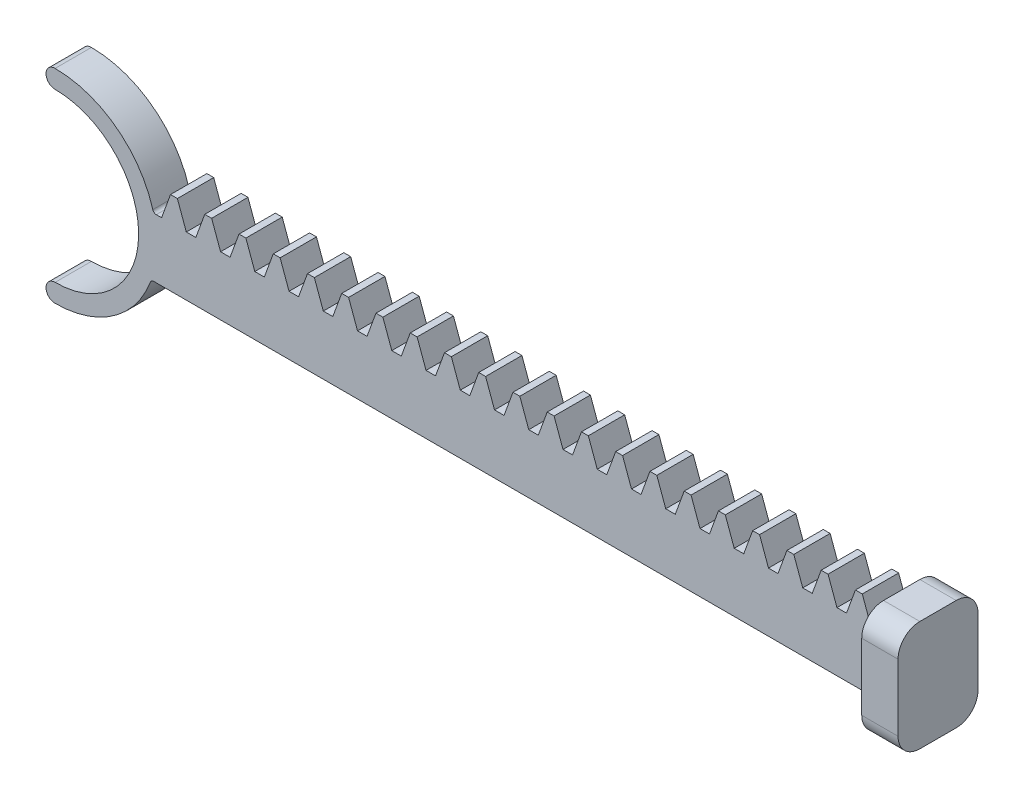
SolidWorks part; units mm, degrees
extrude "Blank" add sketch "BlankSke" against normal blind 5
sketch "BlankSke" plane through (0, 0, 0) normal (0, 0, 1) x (1, 0, 0)
  line L1 (0, 0) -> (100, 0)
  line L2 (0, 0) -> (0, 11.5)
  line L3 (0, 11.5) -> (100, 11.5)
  line L4 (100, 0) -> (100, 11.5)
  dimension "Length" = 100
  dimension "Blank_height" = 11.5
ref_plane "Plane1" through (0, 0, 0) normal (0, 0, 1) x (1, 0, 0)
ref_plane "Plane2" through (0, 0, 0) normal (0, 1, 0) x (1, 0, 0)
ref_plane "Plane3" through (0, 0, 0) normal (1, 0, 0) x (0, 0, -1)
other "Configuration Table"
sketch "HoldingSke" plane through (0, 0, 0) normal (0, 1, 0) x (1, 0, 0)
  line L0 (0, 0) -> (0.0928, 0.6602)
  line L1 (-15, 0) -> (100, 0) construction
  line L2 (0, 0) -> (-2.1039, 2.3779)
  line L3 (0, 0) -> (-11.863, 4.5341)
  line L4 (0, 0) -> (7.9495, 3.3743)
  line L5 (0, 0) -> (-23.7986, -8.8762)
  line L6 (0, 0) -> (-10.5278, -7.1032)
  line L9 (-71.009, 38.7566) -> (22.9603, 72.9586)
  line L10 (-76.2, 3.8779) -> (-66.2, 3.8779)
  line L11 (0, 0) -> (-5, 0)
  line L12 (-76.2, 101.6) -> (-76.147, 101.6)
  line L13 (24.9733, 27.94) -> (52.9518, 28.4284)
  line L14 (24.9733, 27.94) -> (24.9743, 27.94)
  line L15 (24.9733, 27.94) -> (100.4006, 29.5858)
  circle A0 centre (0, 0) radius 19.05
  circle A1 centre (0, 0) radius 5
  circle A2 centre (0, 0) radius 12.7
  dimension "MPH" = 10
  dimension "Diameter" = 38.1
  dimension "Num_teeth" = 23
  dimension "Pitch" = 0.6667
  dimension "Show_teeth" = 998
  dimension "Thickness" = 12.7
  dimension "Ap" = 20
  dimension "Pitch_height" = 10
  dimension "Width" = 5
  dimension "Backlash" = 0.053
  dimension "Addendum_fac" = 1
  dimension "Dedendum_fac" = 1.25
  dimension "Clearance_fac" = 0.25
  dimension "Dedendum_add" = 0.001
  dimension "Length" = 100
  dimension "Module" = 1.5
sketch "TooCutSkeIll" plane through (0, 0, 0) normal (0, 0, 1) x (1, 0, 0)
  line L0 (-1.8687, 11.4605) -> (-0.7447, 8.3724)
  line L1 (-0.3914, 8.125) -> (0.3914, 8.125)
  line L2 (0.7447, 8.3724) -> (1.8687, 11.4605)
  line L3 (100, 11.5) -> (0, 11.5) construction
  line L4 (0, 0) -> (0, 64.897) construction
  line L5 (-13.208, 10) -> (12.954, 10) construction
  line L6 (0, 0) -> (100, 0) construction
  line L7 (1.3371, 10) -> (1.3371, 48.7463) construction
  line L8 (-1.3371, 10) -> (-1.3371, 48.7463) construction
  line L9 (1.9251, 11.5) -> (1.9251, 11.5254)
  line L10 (-1.9251, 11.5) -> (-1.9251, 11.5254)
  line L11 (-1.9251, 11.5254) -> (1.9251, 11.5254)
  arc A0 (0.3914, 8.125) -> (0.7447, 8.3724) centre (0.3914, 8.501) ccw
  arc A1 (-0.7447, 8.3724) -> (-0.3914, 8.125) centre (-0.3914, 8.501) ccw
  arc A2 (1.9251, 11.5) -> (1.8687, 11.4605) centre (1.9251, 11.44) ccw
  arc A3 (-1.8687, 11.4605) -> (-1.9251, 11.5) centre (-1.9251, 11.44) ccw
  dimension "Pitch_height" = 10
  dimension "Addendum_plus" = 1.5254
  dimension "Pressure_angle" = 20
  dimension "Gap_width" = 2.6742
  dimension "Dedendum" = 1.875
extrude "ToothCutIll" [suppressed] cut sketch "TooCutSkeIll" against normal through all
sketch "TooCutSkeSim" plane through (0, 0, 0) normal (0, 0, 1) x (1, 0, 0)
  line L0 (0.6547, 8.125) -> (-0.6547, 8.125)
  line L1 (1.8923, 11.5254) -> (0.6547, 8.125)
  line L2 (0, 17.4625) -> (0, 53.467) construction
  line L3 (1.8923, 11.5254) -> (-1.8923, 11.5254)
  line L6 (-1.8923, 11.5254) -> (-0.6547, 8.125)
  line L9 (-1.3371, 10) -> (1.3371, 10) construction
  line L10 (0, 0) -> (100, 0) construction
  line L11 (1.3371, 10) -> (1.3371, 53.467) construction
  line L12 (-1.3371, 10) -> (-1.3371, 53.467) construction
  dimension "Pitch_height" = 10
  dimension "Addendum_plus" = 1.5254
  dimension "Pressure_angle" = 20
  dimension "Gap_width" = 2.6742
  dimension "Dedendum" = 1.875
extrude "ToothCutSim" cut sketch "TooCutSkeSim" against normal through all
pattern_linear "TeethCuts" count 22 spacing 4.7124 along (1, 0, 0) of "ToothCutIll", "ToothCutSim"
sketch "Esquisse1" plane through (100, 0, 0) normal (1, 0, 0) x (0, 0, -1)
  line L0 (5, 12.1833) -> (0, 12.1833)
  line L1 (-3, 9.1833) -> (-3, 0)
  line L2 (0, -3) -> (5, -3)
  line L3 (8, 0) -> (8, 9.1833)
  line L4 (5, 9.1833) -> (0, 9.1833)
  line L5 (0, 9.1833) -> (0, 0)
  line L6 (0, 0) -> (5, 0)
  line L7 (5, 0) -> (5, 9.1833)
  line L8 (5, 9.1833) -> (0, 9.1833)
  line L9 (0, 9.1833) -> (0, 0) construction
  line L10 (0, 0) -> (5, 0)
  line L11 (5, 0) -> (5, 9.1833)
  line L12 (8, 12.1833) -> (-3, 12.1833) construction
  line L13 (8, -3) -> (8, 12.1833) construction
  line L14 (-3, -3) -> (8, -3) construction
  line L15 (-3, 12.1833) -> (-3, -3) construction
  arc A0 (5, 12.1833) -> (8, 9.1833) centre (5, 9.1833) cw
  arc A1 (5, -3) -> (8, 0) centre (5, 0) ccw
  arc A2 (-3, 0) -> (0, -3) centre (0, 0) ccw
  arc A3 (0, 12.1833) -> (-3, 9.1833) centre (0, 9.1833) ccw
  line M9 (5, 9.1833) -> (0, 9.1833)
  line M10 (0, 9.1833) -> (0, 0)
  line M11 (0, 0) -> (5, 0)
  line M12 (5, 0) -> (5, 9.1833)
  dimension "D3" = 3
  dimension "D1" = 0
  dimension "D2" = 3
extrude "Boss.-Extru.1" add sketch "Esquisse1" along normal blind 5 contours M12 M9 M10 M11 | L2 L3 L0 L1 M9 M12 M11 M10
sketch "Esquisse2" plane through (0, 0, -5) normal (0, 0, -1) x (-1, 0, 0)
  line L0 (-100, 4.5916) -> (14, 4.5916) construction
  line L1 (-100, 0) -> (-100, 9.1833) construction
  line L2 (0, 8.125) -> (0, 0) construction
  line L3 (0, 0) -> (-100, 0) construction
  line L4 (14, 25.3023) -> (14, -17.91) construction
  line L5 (0, 8.125) -> (0.0723, 8.125)
  line L6 (0, 0) -> (0.4234, 0)
  line L7 (0, 8.125) -> (0, 0)
  arc A0 (14, 18.5916) -> (0.5525, 8.4859) centre (14, 4.5916) ccw
  arc A1 (14, 16.0916) -> (14, -6.9084) centre (14, 4.5916) ccw
  arc A2 (14, 18.5916) -> (14, 16.0916) centre (14, 17.3416) cw
  arc A3 (14, -6.9084) -> (14, -9.4084) centre (14, -8.1584) cw
  arc A4 (0.8915, -0.3244) -> (14, -9.4084) centre (14, 4.5916) ccw
  arc A5 (14, 18.5916) -> (14, -9.4084) centre (14, 4.5916) ccw construction
  arc A6 (0.4234, 0) -> (0.8915, -0.3244) centre (0.4234, -0.5) cw
  arc A7 (0.0723, 8.125) -> (0.5525, 8.4859) centre (0.0723, 8.625) ccw
  point P23 (0.7744, 0)
  dimension "D1" = 28
  dimension "D3" = 0.5
  dimension "D2" = 2.5
extrude "Boss.-Extru.2" add sketch "Esquisse2" against normal blind 5
equation "' \"Module@HoldingSke\" = 6.35"
equation "' \"Num_teeth@HoldingSke\" = 12"
equation "' \"Ap@HoldingSke\" =  20"
equation "' \"Ap@HoldingSke\" = 20"
equation "' \"Width@HoldingSke\" = 0.25 * 25.4"
equation "' \"Show_teeth@HoldingSke\" = 500"
equation "' \"Backlash@HoldingSke\" = 0.009 * 25.4"
equation "' \"Addendum_fac@HoldingSke\" = 1.0"
equation "' \"Dedendum_fac@HoldingSke\" = 1.25"
equation "' \"Dedendum_add@HoldingSke\" = 0.00005 * 25.4"
equation "' \"Clearance_fac@HoldingSke\" = 0.25"
equation "' \"Pitch_height@HoldingSke\" = 1 * 25.4"
equation "' \"Length@HoldingSke\" = 4.71 * 25.4"
equation "\"Pitch@HoldingSke\" = 1 / \"Module@HoldingSke\""
equation "\"MPH@HoldingSke\" = \"Dedendum_fac@HoldingSke\" / \"Pitch@HoldingSke\" + 2 * \"Dedendum_add@HoldingSke\" + 0.002 * 25.4"
equation "\"MPH@HoldingSke\" = ((sgn( \"MPH@HoldingSke\" - \"Pitch_height@HoldingSke\")+1)*( \"MPH@HoldingSke\" - \"Pitch_height@HoldingSke\"))/2 + \"Pitch_height@HoldingSke\""
equation "\"Blank_height@BlankSke\" = \"Pitch_height@HoldingSke\" + \"Addendum_fac@HoldingSke\"  / \"Pitch@HoldingSke\" "
equation "\"Length@BlankSke\" =  \"Length@HoldingSke\""
equation "\"Face_width@Blank\" = \"Width@HoldingSke\""
equation "\"Pressure_angle@TooCutSkeIll\" = \"Ap@HoldingSke\""
equation "\"Addendum_plus@TooCutSkeIll\" =  \"Addendum_fac@HoldingSke\"  / \"Pitch@HoldingSke\" + 0.001 *25.4"
equation "\"Dedendum@TooCutSkeIll\" = \"Dedendum_fac@HoldingSke\"  / \"Pitch@HoldingSke\""
equation "\"Pitch_height@TooCutSkeIll\" =  \"MPH@HoldingSke\""
equation "\"Gap_width@TooCutSkeIll\" = 3.14159265 / 2 / \"Pitch@HoldingSke\" + 6 * \"Backlash@HoldingSke\""
equation "\"Pressure_angle@TooCutSkeSim\" = \"Ap@HoldingSke\""
equation "\"Addendum_plus@TooCutSkeSim\" =  \"Addendum_fac@HoldingSke\"  / \"Pitch@HoldingSke\" + 0.001 * 25.4"
equation "\"Dedendum@TooCutSkeSim\" = \"Dedendum_fac@HoldingSke\"  / \"Pitch@HoldingSke\""
equation "\"Pitch_height@TooCutSkeSim\" =  \"MPH@HoldingSke\""
equation "\"Gap_width@TooCutSkeSim\" = 3.14159265 / 2 / \"Pitch@HoldingSke\" + 6 * \"Backlash@HoldingSke\""
equation "\"Root_fillet@TooCutSkeIll\" = \"Clearance_fac@HoldingSke\" / \"Pitch@HoldingSke\" + \"Dedendum_add@HoldingSke\""
equation "\"Break_rad@TooCutSkeIll\" = 0.02 / \"Pitch@HoldingSke\" * 2"
equation "\"Linear_pitch@TeethCuts\" = 3.14159265 / \"Pitch@HoldingSke\""
equation "\"Num_teeth@HoldingSke\" = int( ( \"Length@HoldingSke\" + 0 ) / (3.14159265 / \"Pitch@HoldingSke\")) + 0.9999  + 1"
equation " \"Num_teeth@TeethCuts\" = int( \"Show_teeth@HoldingSke\" ) + 1"
equation " \"Num_teeth@TeethCuts\" = ((sgn( \"Num_teeth@TeethCuts\" - \"Num_teeth@HoldingSke\" )-1)*( \"Num_teeth@TeethCuts\" - \"Num_teeth@HoldingSke\" ))/-2+ \"Num_teeth@HoldingSke\""
equation " \"Num_teeth@TeethCuts\" = ((sgn( \"Num_teeth@TeethCuts\" - 2.0)+1)*( \"Num_teeth@TeethCuts\" - 2.0))/2 +2.0"
